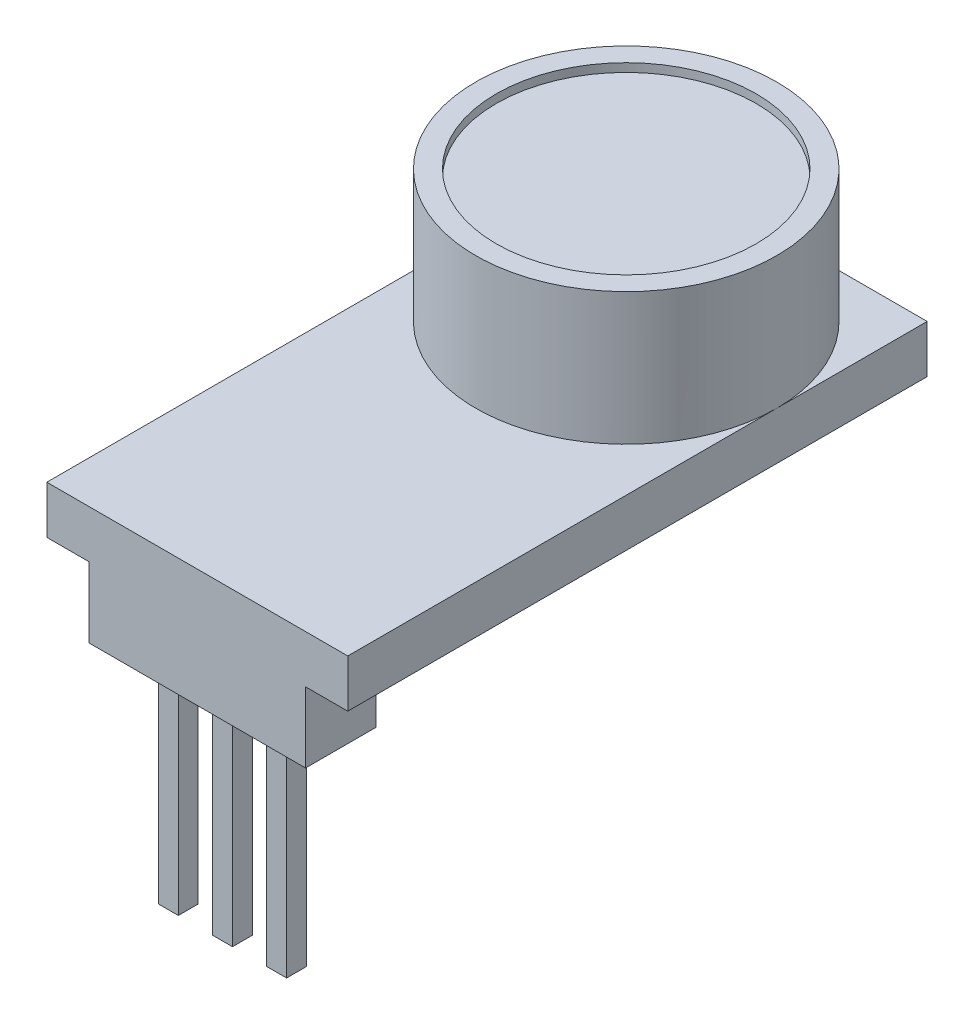
SolidWorks part; units mm, degrees
ref_plane "Front Plane" through (0, 0, 0) normal (0, 0, 1) x (1, 0, 0)
ref_plane "Top Plane" through (0, 0, 0) normal (0, 1, 0) x (1, 0, 0)
ref_plane "Right Plane" through (0, 0, 0) normal (1, 0, 0) x (0, 0, -1)
sketch "Sketch1" plane through (0, 0, 0) normal (0, 1, 0) x (1, 0, 0)
  line L1 (-5.35, -10.3) -> (5.35, -10.3)
  line L2 (-5.35, -10.3) -> (-5.35, 10.3)
  line L3 (-5.35, 10.3) -> (5.35, 10.3)
  line L4 (5.35, -10.3) -> (5.35, 10.3)
  line L5 (-5.35, -10.3) -> (5.35, 10.3) construction
  line L6 (-5.35, 10.3) -> (5.35, -10.3) construction
  point P0 (0, 0)
  dimension "D1" = 10.7
  dimension "D2" = 20.6
extrude "Boss-Extrude1" add sketch "Sketch1" along normal mid plane 1.7
sketch "Sketch2" plane through (0, -0.85, 0) normal (0, -1, 0) x (1, 0, 0)
  line L4 (5.35, -10.3) -> (5.35, 10.3)
  line L5 (5.35, 10.3) -> (-5.35, 10.3)
  line L6 (-5.35, 10.3) -> (-5.35, -10.3)
  line L7 (-5.35, -10.3) -> (5.35, -10.3)
  line L8 (5.35, -10.3) -> (5.35, 10.3) construction
  line L9 (5.35, 10.3) -> (-5.35, 10.3) construction
  line L10 (-5.35, 10.3) -> (-5.35, -10.3) construction
  line L11 (-5.35, -10.3) -> (5.35, -10.3) construction
  circle A0 centre (0, -4.95) radius 5.35
  dimension "D1" = 0
extrude "Boss-Extrude2" add sketch "Sketch2" against normal blind 6.4
sketch "Sketch3" plane through (0, -0.85, 0) normal (0, -1, 0) x (1, 0, 0)
  line L0 (-5.35, 10.3) -> (5.35, 10.3) construction
  line L1 (-3.85, 10.3) -> (3.85, 10.3)
  line L2 (-3.85, 10.3) -> (-3.85, 7.8)
  line L3 (-3.85, 7.8) -> (3.85, 7.8)
  line L4 (3.85, 10.3) -> (3.85, 7.8)
  point P4 (0, 7.8)
  dimension "D1" = 7.7
  dimension "D2" = 2.5
extrude "Boss-Extrude3" add sketch "Sketch3" along normal blind 2.5
sketch "Sketch4" plane through (0, -3.35, 0) normal (0, -1, 0) x (1, 0, 0)
  line L0 (-3.85, 9.05) -> (3.85, 9.05) construction
  line L1 (-3.85, 10.3) -> (-3.85, 7.8) construction
  line L2 (3.85, 7.8) -> (3.85, 10.3) construction
  line L3 (-3.85, 9.05) -> (-1.925, 9.05) construction
  line L4 (-1.925, 9.05) -> (0, 9.05) construction
  line L5 (0, 9.05) -> (1.925, 9.05) construction
  line L6 (1.925, 9.05) -> (3.85, 9.05) construction
  line L8 (-2.2786, 8.6964) -> (-1.5714, 8.6964)
  line L9 (-2.2786, 8.6964) -> (-2.2786, 9.4036)
  line L10 (-2.2786, 9.4036) -> (-1.5714, 9.4036)
  line L11 (-1.5714, 8.6964) -> (-1.5714, 9.4036)
  line L12 (-2.2786, 8.6964) -> (-1.5714, 9.4036) construction
  line L13 (-2.2786, 9.4036) -> (-1.5714, 8.6964) construction
  line L14 (-0.3536, 8.6964) -> (0.3536, 8.6964)
  line L15 (-0.3536, 8.6964) -> (-0.3536, 9.4036)
  line L16 (-0.3536, 9.4036) -> (0.3536, 9.4036)
  line L17 (0.3536, 8.6964) -> (0.3536, 9.4036)
  line L18 (-0.3536, 8.6964) -> (0.3536, 9.4036) construction
  line L19 (-0.3536, 9.4036) -> (0.3536, 8.6964) construction
  line L20 (1.5714, 8.6964) -> (2.2786, 8.6964)
  line L21 (1.5714, 8.6964) -> (1.5714, 9.4036)
  line L22 (1.5714, 9.4036) -> (2.2786, 9.4036)
  line L23 (2.2786, 8.6964) -> (2.2786, 9.4036)
  line L24 (1.5714, 8.6964) -> (2.2786, 9.4036) construction
  line L25 (1.5714, 9.4036) -> (2.2786, 8.6964) construction
  circle A0 centre (-1.925, 9.05) radius 0.5 construction
  circle A1 centre (0, 9.05) radius 0.5 construction
  circle A2 centre (1.925, 9.05) radius 0.5 construction
  dimension "D1" = 1
extrude "Boss-Extrude4" add sketch "Sketch4" along normal blind 7.7
sketch "Sketch5" plane through (0, 5.55, 0) normal (0, 1, 0) x (1, 0, 0)
  circle A0 centre (0, 4.95) radius 4.6209
extrude "Cut-Extrude1" cut sketch "Sketch5" against normal blind 0.3
